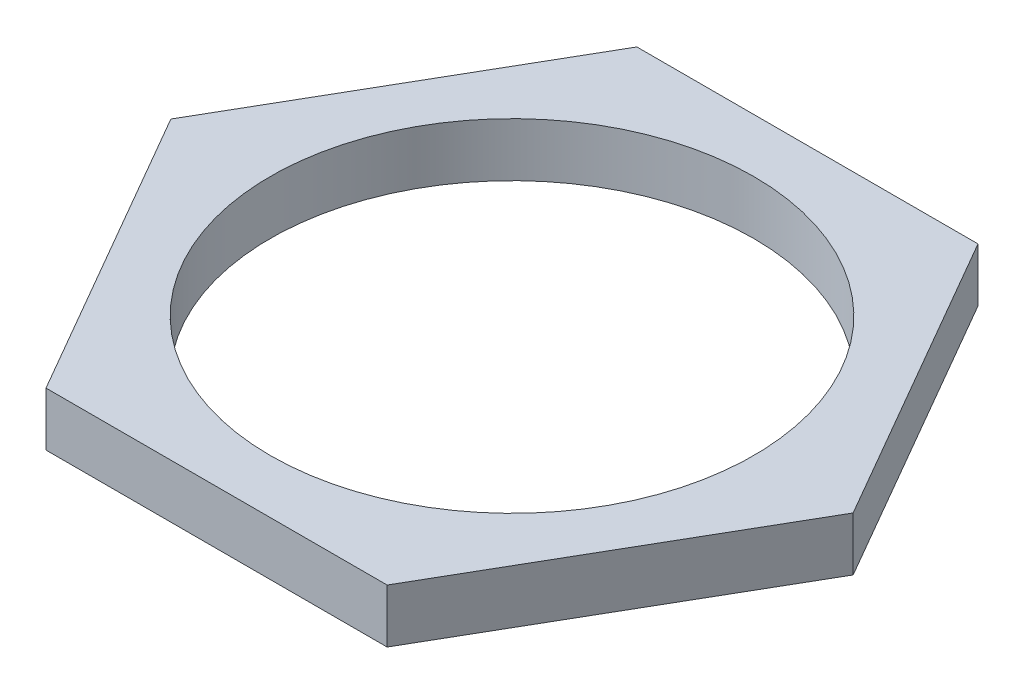
SolidWorks part; units mm, degrees
ref_plane "Front Plane" through (0, 0, 0) normal (0, 0, 1) x (1, 0, 0)
ref_plane "Top Plane" through (0, 0, 0) normal (0, 1, 0) x (1, 0, 0)
ref_plane "Right Plane" through (0, 0, 0) normal (1, 0, 0) x (0, 0, -1)
sketch "Sketch1" plane through (0, 0, 0) normal (0, 1, 0) x (1, 0, 0)
  line L1 (6.3509, -11) -> (12.7017, 0)
  line L2 (12.7017, 0) -> (6.3509, 11)
  line L3 (6.3509, 11) -> (-6.3509, 11)
  line L4 (-6.3509, 11) -> (-12.7017, 0)
  line L5 (-12.7017, 0) -> (-6.3509, -11)
  line L6 (-6.3509, -11) -> (6.3509, -11)
  circle A0 centre (0, 0) radius 11 construction
  circle A1 centre (0, 0) radius 9
  dimension "D2" = 18
  dimension "D1" = 22
extrude "Boss-Extrude1" add sketch "Sketch1" along normal blind 2
